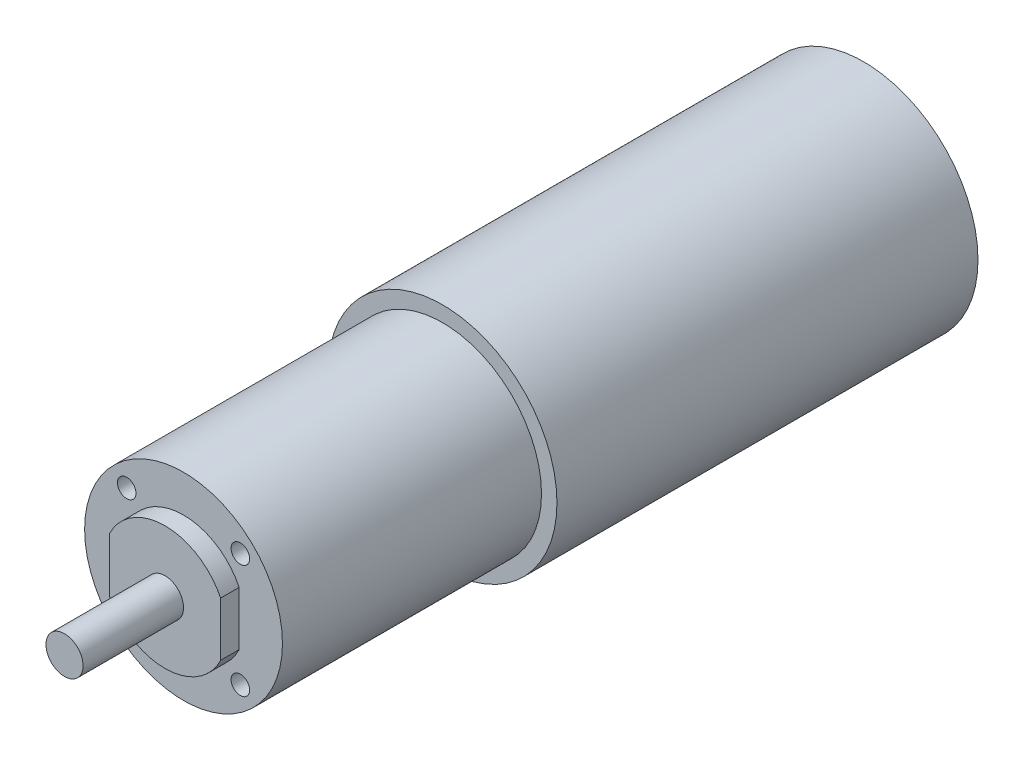
SolidWorks part; units mm, degrees
ref_plane "Front Plane" through (0, 0, 0) normal (0, 0, 1) x (1, 0, 0)
ref_plane "Top Plane" through (0, 0, 0) normal (0, 1, 0) x (1, 0, 0)
ref_plane "Right Plane" through (0, 0, 0) normal (1, 0, 0) x (0, 0, -1)
sketch "Sketch1" plane through (0, 0, 0) normal (0, 0, 1) x (1, 0, 0)
  circle A0 centre (0, 0) radius 16
  dimension "D1" = 32
extrude "Boss-Extrude1" add sketch "Sketch1" along normal blind 41.9 contours A0
sketch "Sketch2" plane through (0, 0, 41.9) normal (0, 0, 1) x (1, 0, 0)
  line L1 (9.1924, 9.1924) -> (-9.1924, 9.1924) construction
  line L2 (9.1924, 9.1924) -> (9.1924, -9.1924) construction
  line L3 (9.1924, -9.1924) -> (-9.1924, -9.1924) construction
  line L4 (-9.1924, 9.1924) -> (-9.1924, -9.1924) construction
  line L5 (9.1924, 9.1924) -> (-9.1924, -9.1924) construction
  line L6 (9.1924, -9.1924) -> (-9.1924, 9.1924) construction
  circle A0 centre (-9.1924, 9.1924) radius 1.5
  circle A1 centre (9.1924, 9.1924) radius 1.5
  circle A2 centre (9.1924, -9.1924) radius 1.5
  circle A3 centre (-9.1924, -9.1924) radius 1.5
  point P0 (0, 0)
  dimension "D2" = 3
  dimension "D1" = 26
extrude "Cut-Extrude1" cut sketch "Sketch2" against normal blind 5
sketch "Sketch3" plane through (0, 0, 41.9) normal (0, 0, 1) x (1, 0, 0)
  line L0 (9, 4.3589) -> (9, -4.3589)
  line L1 (-9, 4.3589) -> (-9, -4.3589)
  line L2 (0, 0) -> (-9, 0) construction
  line L3 (0, 0) -> (9, 0) construction
  arc A0 (-9, -4.3589) -> (9, -4.3589) centre (0, 0) ccw
  arc A1 (9, 4.3589) -> (-9, 4.3589) centre (0, 0) ccw
  dimension "D1" = 20
  dimension "D2" = 18
extrude "Boss-Extrude2" add sketch "Sketch3" along normal blind 3
sketch "Sketch4" plane through (0, 0, 44.9) normal (0, 0, 1) x (1, 0, 0)
  circle A0 centre (0, 0) radius 3
  dimension "D1" = 6
extrude "Boss-Extrude3" add sketch "Sketch4" along normal blind 16.25
sketch "Sketch5" plane through (0, 0, 0) normal (0, 0, -1) x (-1, 0, 0)
  circle A0 centre (0, 0) radius 18.5
  dimension "D1" = 37
extrude "Boss-Extrude4" add sketch "Sketch5" along normal blind 68.1
